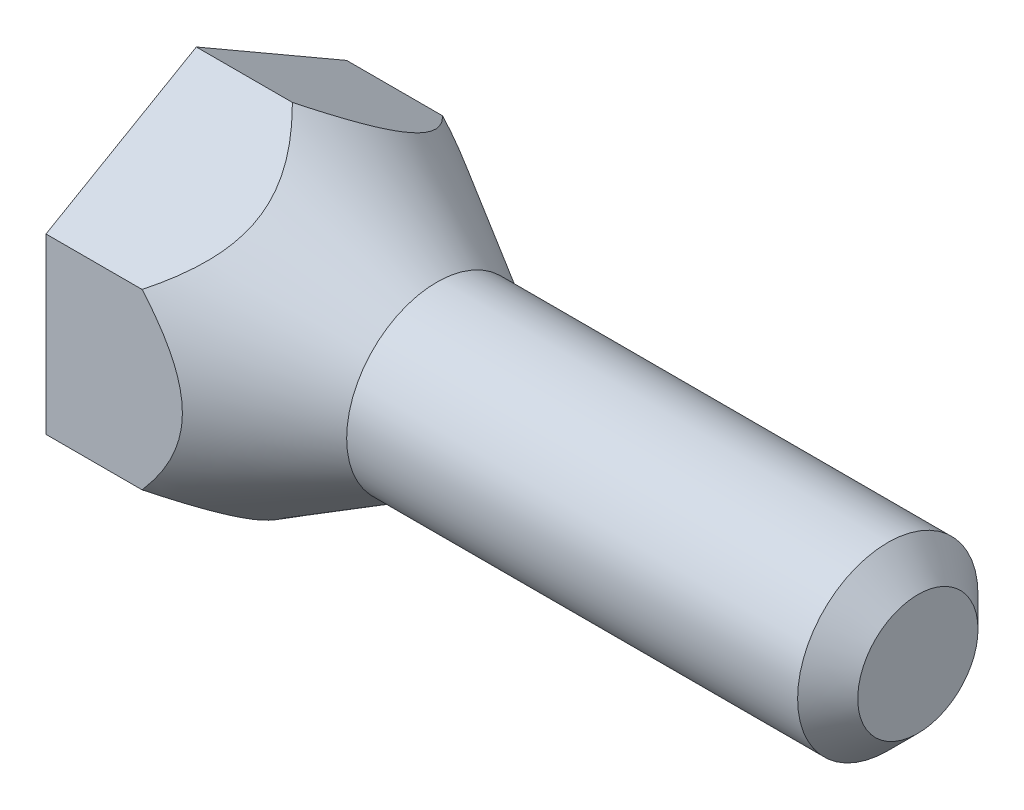
SolidWorks part; units mm, degrees
material "Простая углеродистая сталь"
ref_plane "Спереди" through (0, 0, 0) normal (0, 0, 1) x (1, 0, 0)
ref_plane "Сверху" through (0, 0, 0) normal (0, 1, 0) x (1, 0, 0)
ref_plane "Справа" through (0, 0, 0) normal (1, 0, 0) x (0, 0, -1)
sketch "Эскиз1" plane through (0, 0, 0) normal (1, 0, 0) x (0, 0, -1)
  line L1 (0, 5.7735) -> (-5, 2.8868)
  line L2 (-5, 2.8868) -> (-5, -2.8868)
  line L3 (-5, -2.8868) -> (0, -5.7735)
  line L4 (0, -5.7735) -> (5, -2.8868)
  line L5 (5, -2.8868) -> (5, 2.8868)
  line L6 (5, 2.8868) -> (0, 5.7735)
  circle A0 centre (0, 0) radius 5 construction
  dimension "D1" = 10
extrude "Бобышка-Вытянуть1" add sketch "Эскиз1" along normal blind 24
sketch "Эскиз2" plane through (0, 0, 0) normal (0, 0, 1) x (1, 0, 0)
  line L0 (0, 0) -> (27.107, 0) construction
  line L1 (3.1962, 5.7735) -> (8, 3)
  line L2 (24, 5.7735) -> (0, 5.7735) construction
  line L3 (8, 3) -> (24, 3)
  line L4 (24, 3) -> (24, 5.7735)
  line L5 (24, 5.7735) -> (3.1962, 5.7735)
  dimension "D1" = 6
  dimension "D2" = 30
  dimension "D3" = 16
revolve "Вырез-Повернуть1" cut sketch "Эскиз2" angle 360 about L0
cosmetic thread "Условное изображение резьбы1" parameters "D1"=11, "D2"=4.891
chamfer "Фаска1" distance 1 angle 45 1 edges at (24, 0, 3)
